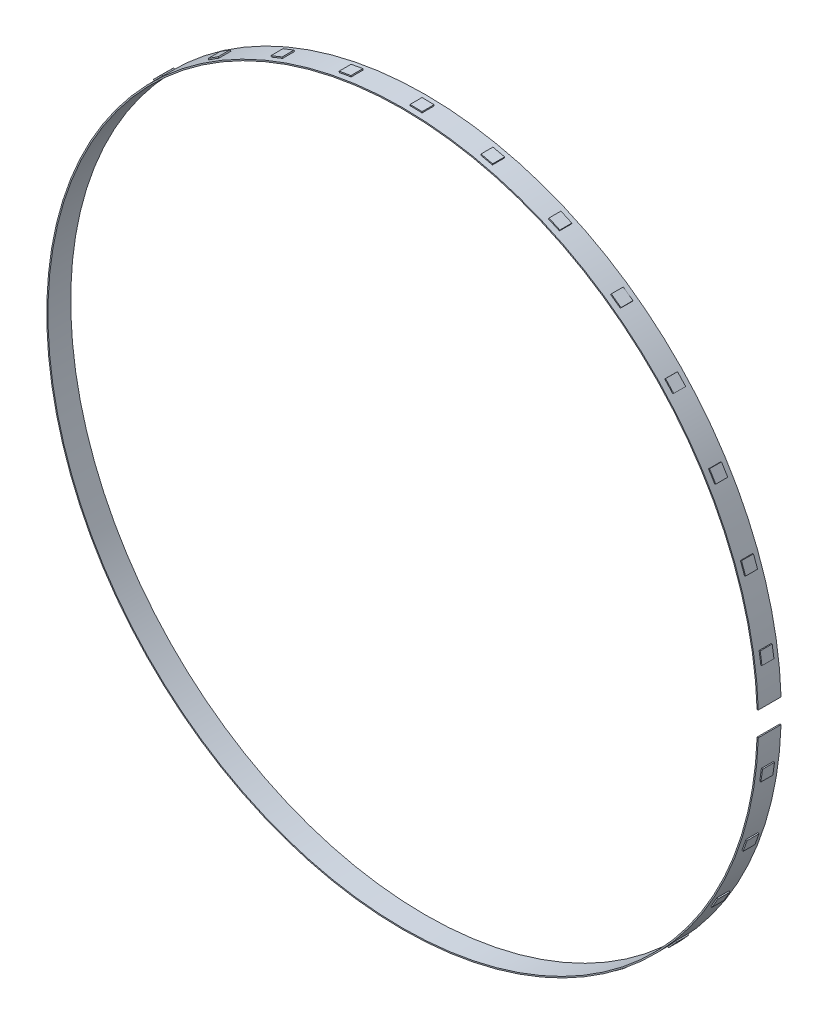
SolidWorks part; units mm, degrees
ref_plane "Plan de face" through (0, 0, 0) normal (0, 0, 1) x (1, 0, 0)
ref_plane "Plan de dessus" through (0, 0, 0) normal (0, 1, 0) x (1, 0, 0)
ref_plane "Plan de droite" through (0, 0, 0) normal (1, 0, 0) x (0, 0, -1)
sketch "Esquisse1" plane through (0, 0, 0) normal (0, 0, 1) x (1, 0, 0)
  line L0 (147.9155, 5) -> (147.9155, -5) construction
  line L1 (148.4158, 5) -> (148.4158, -5) construction
  line L2 (148.4158, 5) -> (147.9155, 5)
  line L3 (147.9155, -5) -> (148.4158, -5)
  arc A0 (147.9155, -5) -> (147.9155, 5) centre (0, 0) cw
  arc A1 (148.4158, 5) -> (148.4158, -5) centre (0, 0) ccw
  dimension "D2" = 148
  dimension "D3" = 0.5
  dimension "D1" = 10
extrude "Boss.-Extru.1" add sketch "Esquisse1" along normal blind 9.5
ref_plane "Plan1" through (0, 0, 2.25) normal (0, 0, 1) x (1, 0, 0)
sketch "Esquisse2" plane through (0, 0, 2.25) normal (0, 0, 1) x (1, 0, 0)
  line L0 (146.9604, 24.5177) -> (147.7003, 19.5728)
  line L1 (147.7003, 19.5728) -> (147.2141, 19.5)
  line L2 (146.9604, 24.5177) -> (146.4742, 24.4449)
  line L3 (147.9155, 5) -> (148.4158, 5) construction
  line L4 (147.9155, 5) -> (148.4158, 5) construction
  line L5 (147.2141, 19.5) -> (148.4158, 5) construction
  line L6 (146.4742, 24.4449) -> (147.2141, 19.5)
  arc A0 (148.4158, 5) -> (148.4158, -5) centre (0, 0) ccw construction
  dimension "D1" = 14.5
  dimension "D2" = 5
extrude "Boss.-Extru.2" add sketch "Esquisse2" along normal blind 5
pattern_circular "Répétition circulaire1" count 31 every 11.456 about axis through (0, 0, 0) along (0, 0, 1) of "Boss.-Extru.2"
